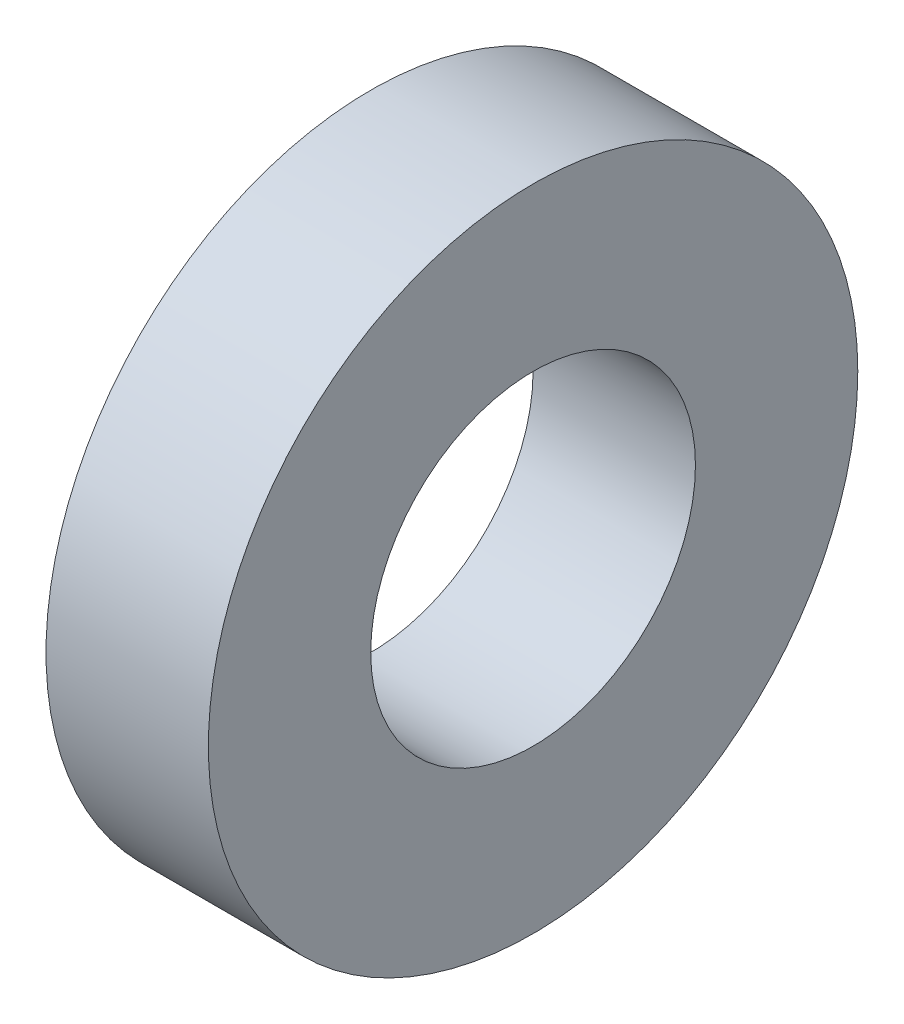
SolidWorks part; units mm, degrees
ref_plane "Front Plane" through (0, 0, 0) normal (0, 0, 1) x (1, 0, 0)
ref_plane "Top Plane" through (0, 0, 0) normal (0, 1, 0) x (1, 0, 0)
ref_plane "Right Plane" through (0, 0, 0) normal (1, 0, 0) x (0, 0, -1)
sketch "Sketch1" plane through (0, 0, 0) normal (1, 0, 0) x (0, 0, -1)
  circle A0 centre (0, 0) radius 10
  circle A1 centre (0, 0) radius 20
  dimension "D1" = 20
  dimension "D2" = 10
extrude "Boss-Extrude1" add sketch "Sketch1" along normal blind 10
